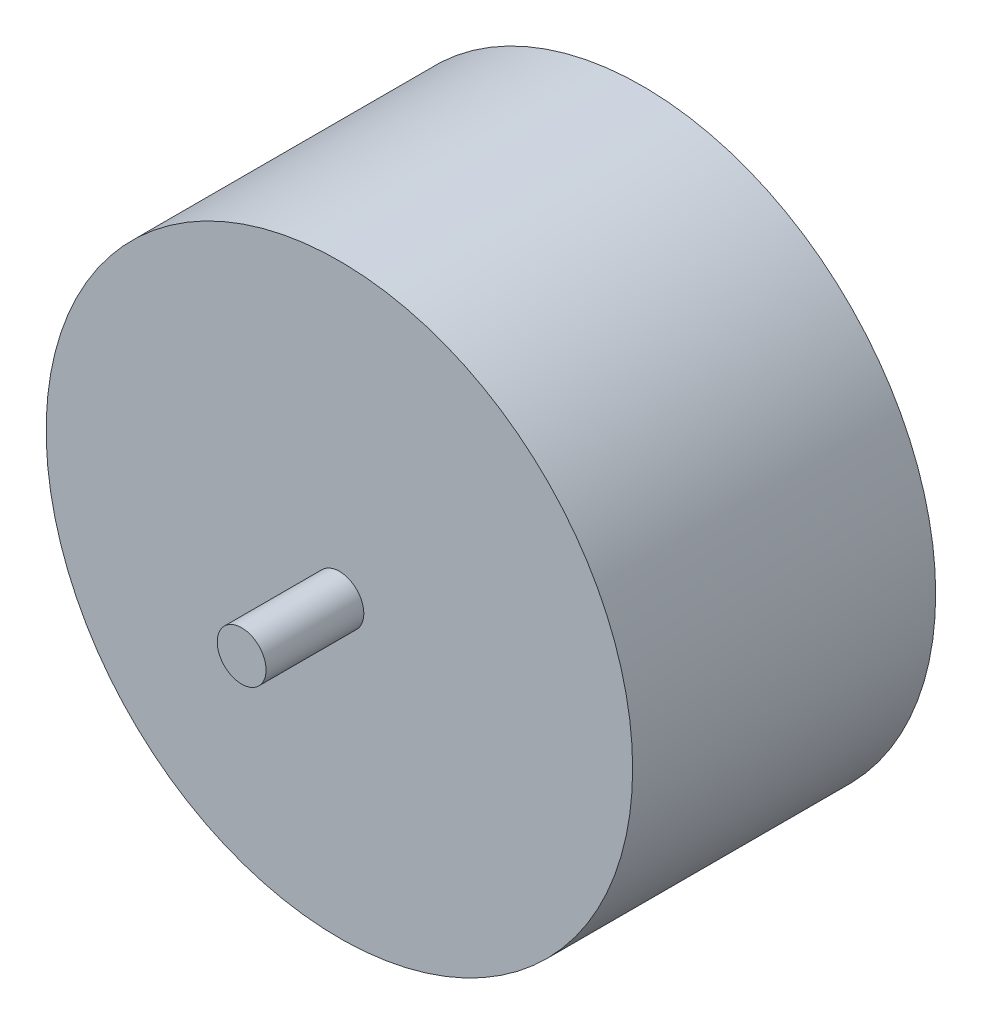
SolidWorks part; units mm, degrees
ref_plane "前视基准面" through (0, 0, 0) normal (0, 0, 1) x (1, 0, 0)
ref_plane "上视基准面" through (0, 0, 0) normal (0, 1, 0) x (1, 0, 0)
ref_plane "右视基准面" through (0, 0, 0) normal (1, 0, 0) x (0, 0, -1)
sketch "草图2" plane through (0, 0, 0) normal (0, 0, 1) x (1, 0, 0)
  circle A0 centre (0, 0) radius 30
  dimension "D1" = 60
extrude "凸台-拉伸1" add sketch "草图2" along normal blind 31
sketch "草图3" plane through (0, 0, 31) normal (0, 0, 1) x (1, 0, 0)
  circle A0 centre (0, 0) radius 2.5
  dimension "D1" = 5
extrude "凸台-拉伸2" add sketch "草图3" along normal blind 10
